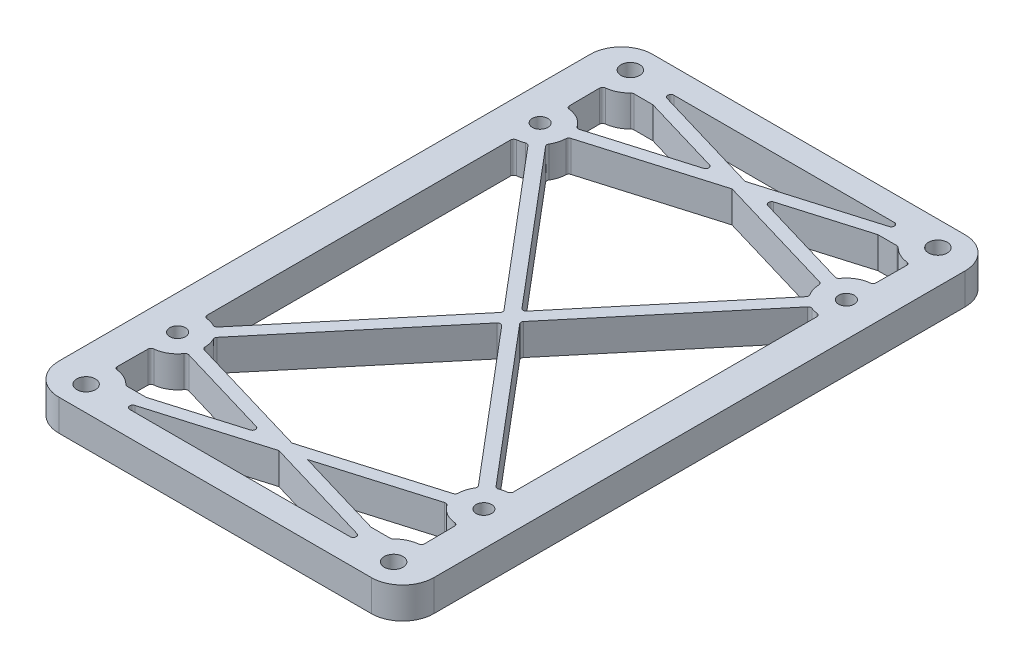
SolidWorks part; units mm, degrees
ref_plane "前视基准面" through (0, 0, 0) normal (0, 0, 1) x (1, 0, 0)
ref_plane "上视基准面" through (0, 0, 0) normal (0, 1, 0) x (1, 0, 0)
ref_plane "右视基准面" through (0, 0, 0) normal (1, 0, 0) x (0, 0, -1)
sketch "草图1" plane through (0, 0, 0) normal (0, 1, 0) x (1, 0, 0)
  line L1 (30, -47.5) -> (-30, -47.5)
  line L2 (30, -47.5) -> (30, 47.5)
  line L3 (30, 47.5) -> (-30, 47.5)
  line L4 (-30, -47.5) -> (-30, 47.5)
  line L5 (0, 47.5) -> (0, -47.5) construction
  line L6 (30, 0) -> (-30, 0) construction
  point P0 (0, 0)
  dimension "D1" = 60
  dimension "D2" = 95
extrude "凸台-拉伸1" add sketch "草图1" along normal blind 5
sketch "草图2" plane through (0, 5, 0) normal (0, 1, 0) x (1, 0, 0)
  line L0 (0, 50.2017) -> (0, -52.9643) construction
  line L1 (-38.5457, 0) -> (51.3248, 0) construction
  circle A0 centre (-24.605, 43.54) radius 1.5
  circle A1 centre (24.605, 43.54) radius 1.5
  circle A2 centre (24.605, -43.54) radius 1.5
  circle A3 centre (-24.605, -43.54) radius 1.5
  circle A4 centre (-24.5, 29) radius 1.25
  circle A5 centre (24.5, 29) radius 1.25
  circle A6 centre (24.5, -29) radius 1.25
  circle A7 centre (-24.5, -29) radius 1.25
  dimension "D1" = 24.605
  dimension "D3" = 24.5
  dimension "D4" = 29
  dimension "D2" = 43.54
extrude "切除-拉伸1" cut sketch "草图2" against normal blind 5
fillet "圆角1" radius 5 4 edges at (-30, 2.5, 47.5) (30, 2.5, 47.5) (30, 2.5, -47.5) (-30, 2.5, -47.5)
sketch "草图3" plane through (0, 0, 0) normal (0, -1, 0) x (1, 0, 0)
  line L0 (-24.605, 43.54) -> (-24.5, 29)
  line L1 (-27.6049, 43.5183) -> (-27.4999, 28.9783)
  line L2 (-21.6051, 43.5617) -> (-21.5001, 29.0217)
  line L3 (24.605, 43.54) -> (24.5, 29)
  line L4 (21.6051, 43.5617) -> (21.5001, 29.0217)
  line L5 (27.6049, 43.5183) -> (27.4999, 28.9783)
  line L6 (-24.5, 29) -> (-24.5, -29)
  line L7 (-27.5, 29) -> (-27.5, -29)
  line L8 (-21.5, 29) -> (-21.5, -29)
  line L9 (-24.5, -29) -> (-24.605, -43.54)
  line L10 (-27.4999, -28.9783) -> (-27.6049, -43.5183)
  line L11 (-21.5001, -29.0217) -> (-21.6051, -43.5617)
  line L12 (24.5, 29) -> (24.5, -29)
  line L13 (21.5, 29) -> (21.5, -29)
  line L14 (27.5, 29) -> (27.5, -29)
  line L15 (24.5, -29) -> (24.605, -43.54)
  line L16 (21.5001, -29.0217) -> (21.6051, -43.5617)
  line L17 (27.4999, -28.9783) -> (27.6049, -43.5183)
  line L18 (-17.6331, 43.54) -> (17.6331, 43.54)
  line L19 (-24.605, 40.54) -> (24.605, 40.54)
  line L20 (-24.605, 46.54) -> (24.605, 46.54)
  line L21 (-24.5, 29) -> (-20.25, 29)
  line L22 (-24.5, 26) -> (-21.4896, 26)
  line L23 (-24.5, 32) -> (-21.4896, 32)
  line L24 (-24.5, -29) -> (-20.25, -29)
  line L25 (21.4896, 26) -> (24.5, 26)
  line L26 (-24.5, 26) -> (24.5, 26) construction
  line L27 (20.25, 29) -> (24.5, 29)
  line L28 (-24.5, 29) -> (24.5, 29) construction
  line L29 (21.4896, 32) -> (24.5, 32)
  line L30 (-24.5, 32) -> (24.5, 32) construction
  line L31 (20.25, -29) -> (24.5, -29)
  line L32 (-17.6331, -43.54) -> (17.6331, -43.54)
  line L33 (-24.605, -46.54) -> (24.605, -46.54)
  line L34 (-24.605, -40.54) -> (24.605, -40.54)
  line L35 (-24.605, 43.54) -> (24.5, 29)
  line L36 (-24.8889, 42.5812) -> (24.2161, 28.0412)
  line L37 (-17.7751, 42.5606) -> (24.7839, 29.9588)
  line L38 (24.5, 29) -> (-24.5, -29)
  line L39 (23.7361, 29.6454) -> (-25.2639, -28.3546)
  line L40 (25.2639, 28.3546) -> (-23.7361, -29.6454)
  line L41 (-24.5, -29) -> (24.605, -43.54)
  line L42 (-24.7839, -29.9588) -> (17.7751, -42.5606)
  line L43 (-24.2161, -28.0412) -> (24.8889, -42.5812)
  line L44 (24.605, 43.54) -> (-24.5, 29)
  line L45 (17.7751, 42.5606) -> (-24.7839, 29.9588)
  line L46 (24.8889, 42.5812) -> (-24.2161, 28.0412)
  line L47 (-24.7839, 29.9588) -> (24.5, -29)
  line L48 (-25.5512, 29.3175) -> (23.7327, -29.6413)
  line L49 (-24.0167, 30.6002) -> (25.2673, -28.3587)
  line L50 (24.5, -29) -> (-24.605, -43.54)
  line L51 (24.2161, -28.0412) -> (-24.8889, -42.5812)
  line L52 (24.7839, -29.9588) -> (-17.7751, -42.5606)
  line L53 (-24.3211, 44.4988) -> (24.7839, 29.9588) construction
  line L54 (-24.605, 43.54) -> (24.605, 43.54) construction
  line L55 (24.3211, 44.4988) -> (-24.7839, 29.9588) construction
  line L56 (-24.605, -43.54) -> (24.605, -43.54) construction
  line L57 (-24.7839, -29.9588) -> (24.3211, -44.4988) construction
  line L58 (24.7839, -29.9588) -> (-24.3211, -44.4988) construction
  arc A1 (-17.7751, 42.5606) -> (-17.6331, 43.54) centre (-17.6331, 43.04) cw
  circle A2 centre (-24.605, 43.54) radius 4.5
  circle A3 centre (-24.605, 43.54) radius 4.5
  arc A4 (17.7751, 42.5606) -> (17.6331, 43.54) centre (17.6331, 43.04) ccw
  arc A5 (17.6331, -43.54) -> (17.7751, -42.5606) centre (17.6331, -43.04) ccw
  arc A6 (-17.6331, -43.54) -> (-17.7751, -42.5606) centre (-17.6331, -43.04) cw
  circle A8 centre (24.605, 43.54) radius 4.5
  circle A9 centre (24.605, 43.54) radius 4.5
  circle A11 centre (-24.5, 29) radius 4.25
  circle A12 centre (-24.5, 29) radius 4.25
  circle A14 centre (24.5, 29) radius 4.25
  circle A15 centre (24.5, 29) radius 4.25
  circle A17 centre (-24.5, -29) radius 4.25
  circle A18 centre (-24.5, -29) radius 4.25
  circle A20 centre (24.5, -29) radius 4.25
  circle A21 centre (24.5, -29) radius 4.25
  circle A23 centre (-24.605, -43.54) radius 4.5
  circle A24 centre (-24.605, -43.54) radius 4.5
  circle A26 centre (24.605, -43.54) radius 4.5
  circle A27 centre (24.605, -43.54) radius 4.5
  point P92 (-23.2511, 44.1857)
  dimension "D39" = 0.5
  dimension "D40" = 0.5
  dimension "D41" = 0.5
  dimension "D1" = 3
  dimension "D2" = 3
  dimension "D3" = 3
  dimension "D4" = 3
  dimension "D5" = 3
  dimension "D6" = 3
  dimension "D7" = 3
  dimension "D8" = 3
  dimension "D9" = 3
  dimension "D10" = 3
  dimension "D11" = 3
  dimension "D12" = 3
  dimension "D13" = 3
  dimension "D14" = 3
  dimension "D15" = 3
  dimension "D16" = 3
  dimension "D17" = 3
  dimension "D18" = 3
  dimension "D19" = 3
  dimension "D20" = 3
  dimension "D21" = 3
  dimension "D22" = 3
  dimension "D23" = 3
  dimension "D24" = 3
  dimension "D25" = 3
  dimension "D26" = 3
  dimension "D27" = 1
  dimension "D28" = 1
  dimension "D29" = 1
  dimension "D30" = 1
  dimension "D31" = 1
  dimension "D32" = 1
  dimension "D33" = 1
  dimension "D34" = 1
  dimension "D35" = 1
  dimension "D36" = 1
  dimension "D37" = 1
  dimension "D38" = 1
extrude "切除-拉伸4" cut sketch "草图3" against normal blind 5 contours A15 L4 A9 L19 L46 L37 | A12 L45 L36 L19 A3 L2 | L45 L19 L37 | A9 L18 A3 L37 L19 L45 | A15 L36 L46 A12 L49 L39 | L48 L8 L39 | L40 L49 L13 | A21 L12 A15 L40 L13 L49 | A18 L39 L8 L48 A12 L6 | A21 L48 L40 A18 L43 L51 | A24 L34 L51 L42 A18 L11 | A27 L16 A21 L52 L43 L34 | L42 L52 L34 | A27 L42 L34 L52 A24 L32 | A24 L11 A18 L9 | A12 L2 A3 L0 | A15 L3 A9 L4 | A27 L15 A21 L16
fillet "圆角4" radius 0.5 19 edges at (-24.5725, 2.5, -39.0401) (-21.2509, 2.5, -40.54) (-3.5222, 2.5, -36.2545) (-24.5307, 2.5, -33.2499) (-20.8232, 2.5, -31.1316) (-20.2554, 2.5, -29.2139) (-21.0704, 2.5, -26.49) (-24.5, 2.5, -24.75) (-22.5981, 2.5, -25.1993) (-1.1761, 2.5, 0.1574) (-24.5, 2.5, 24.75) (-22.2644, 2.5, 25.3855) (-20.8538, 2.5, 26.8165) (-20.2554, 2.5, 29.2139) (-24.5307, 2.5, 33.2499) (-20.8232, 2.5, 31.1316) (-24.5725, 2.5, 39.0401) (-21.2509, 2.5, 40.54) (-3.5222, 2.5, 36.2545)
fillet "圆角5" radius 0.5 20 edges at (21.2509, 2.5, 40.54) (24.5725, 2.5, 39.0401) (24.5307, 2.5, 33.2499) (20.8232, 2.5, 31.1316) (21.0704, 2.5, 26.49) (20.2554, 2.5, 29.2139) (22.5981, 2.5, 25.1993) (24.5, 2.5, 24.75) (0.1341, 2.5, 1.7083) (0.126, 2.5, -1.4004) (1.4363, 2.5, 0.1506) (24.5, 2.5, -24.75) (22.6181, 2.5, -25.1894) (21.0835, 2.5, -26.4721) (20.2554, 2.5, -29.2139) (20.8232, 2.5, -31.1316) (24.5307, 2.5, -33.2499) (24.5725, 2.5, -39.0401) (21.2509, 2.5, -40.54) (3.5222, 2.5, -36.2545)
